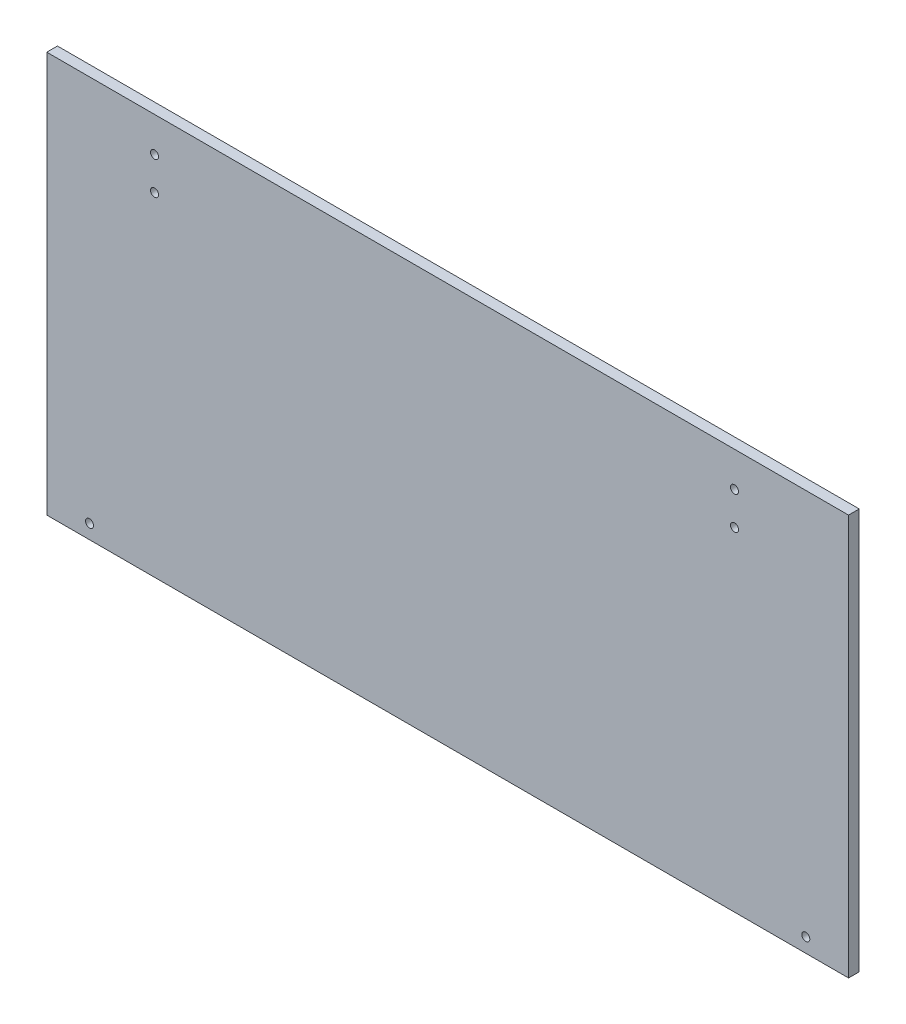
SolidWorks part; units mm, degrees
material "Pino"
ref_plane "Piano frontale" through (0, 0, 0) normal (0, 0, 1) x (1, 0, 0)
ref_plane "Piano superiore" through (0, 0, 0) normal (0, 1, 0) x (1, 0, 0)
ref_plane "Piano destro" through (0, 0, 0) normal (1, 0, 0) x (0, 0, -1)
sketch "Schizzo1" plane through (0, 0, 0) normal (0, 0, 1) x (1, 0, 0)
  line L5 (-225, 112.5) -> (225, 112.5)
  line L6 (-225, 112.5) -> (-225, -112.5)
  line L7 (-225, -112.5) -> (225, -112.5)
  line L8 (225, 112.5) -> (225, -112.5)
  line L9 (-225, 112.5) -> (225, -112.5) construction
  line L10 (-225, -112.5) -> (225, 112.5) construction
  point P8 (0, 0)
  dimension "D1" = 225
  dimension "D2" = 450
extrude "Estrusione-Estrusione1" add sketch "Schizzo1" along normal blind 6
sketch "Schizzo2" plane through (0, 0, 0) normal (0, 0, -1) x (-1, 0, 0)
  circle A0 centre (-161, 93) radius 2.25
  circle A1 centre (-161, 74.5) radius 2.25
  circle A2 centre (164.5, 93) radius 2.25
  circle A3 centre (164.5, 74.5) radius 2.25
  dimension "D1" = 4.5
extrude "Taglio-Estrusione1" cut sketch "Schizzo2" against normal blind 10
sketch "Schizzo3" plane through (0, 0, 0) normal (0, 0, -1) x (-1, 0, 0)
  line L0 (201, -104.5) -> (-201, -104.5) construction
  line L1 (225, -112.5) -> (-225, -112.5) construction
  line L2 (225, 112.5) -> (225, -112.5) construction
  line L3 (-225, -112.5) -> (-225, 112.5) construction
  circle A0 centre (201, -104.5) radius 2.25
  circle A1 centre (-201, -104.5) radius 2.25
  dimension "D1" = 4.5
  dimension "D2" = 8
  dimension "D3" = 24
  dimension "D4" = 24
extrude "Taglio-Estrusione2" cut sketch "Schizzo3" against normal blind 10
